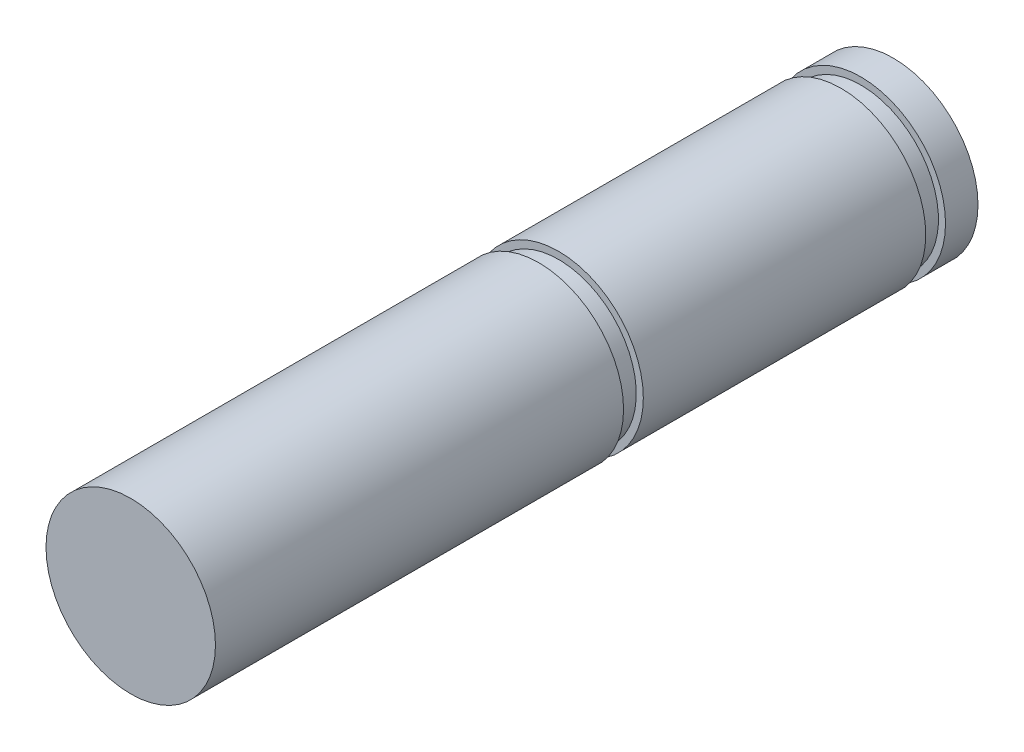
SolidWorks part; units mm, degrees
ref_plane "정면" through (0, 0, 0) normal (0, 0, 1) x (1, 0, 0)
ref_plane "윗면" through (0, 0, 0) normal (0, 1, 0) x (1, 0, 0)
ref_plane "우측면" through (0, 0, 0) normal (1, 0, 0) x (0, 0, -1)
sketch "스케치1" plane through (0, 0, 0) normal (0, 0, 1) x (1, 0, 0)
  circle A0 centre (0, 0) radius 3
  dimension "D1" = 6
extrude "보스-돌출1" add sketch "스케치1" along normal blind 27
ref_plane "평면1" through (0, 0, 1.5) normal (0, 0, -1) x (-1, 0, 0)
sketch "스케치2" plane through (0, 0, 1.5) normal (0, 0, -1) x (-1, 0, 0)
  circle A0 centre (0, 0) radius 2.75
  circle A1 centre (0, 0) radius 3
  circle A2 centre (0, 0) radius 3
  dimension "D1" = 0
  dimension "D2" = 0.25
extrude "컷-돌출1" cut sketch "스케치2" against normal blind 0.35 and the other way blind 0.35
ref_plane "평면2" through (0, 0, 11.85) normal (0, 0, -1) x (-1, 0, 0)
sketch "스케치3" plane through (0, 0, 11.85) normal (0, 0, -1) x (-1, 0, 0)
  circle A0 centre (0, 0) radius 2.75
  circle A1 centre (0, 0) radius 3
  circle A2 centre (0, 0) radius 3
  dimension "D1" = 0
  dimension "D2" = 0.25
extrude "컷-돌출2" cut sketch "스케치3" against normal blind 0.7
